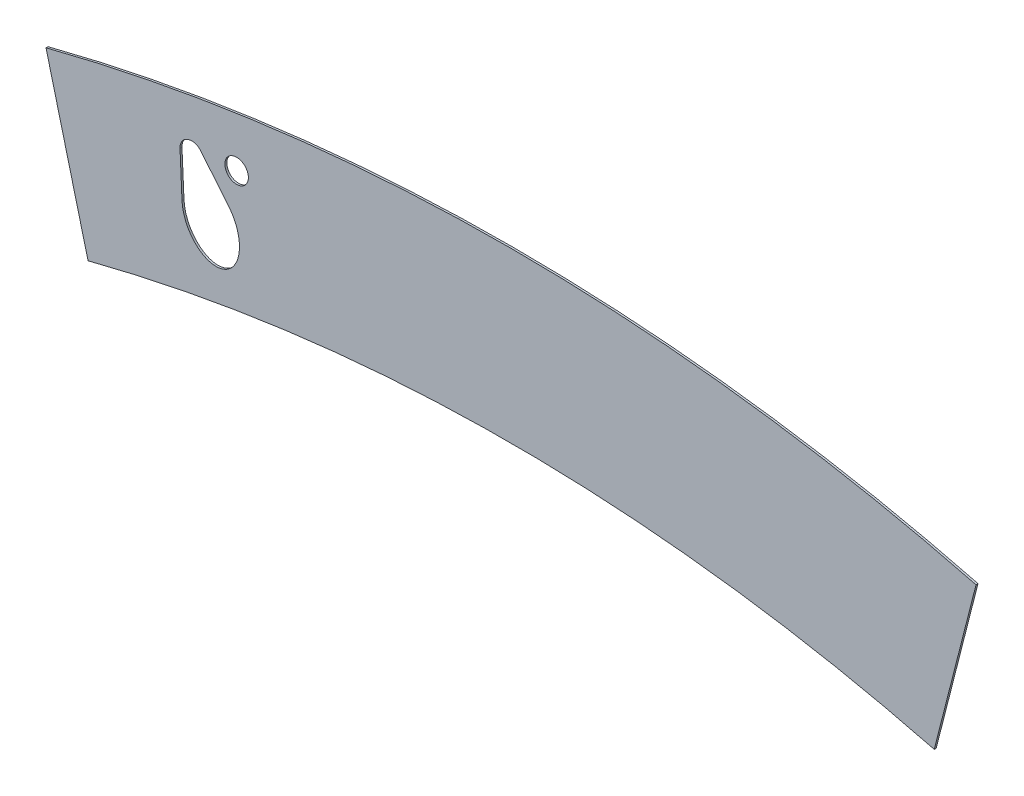
SolidWorks part; units mm, degrees
material "6061 Alloy"
ref_plane "front" through (0, 0, 0) normal (0, 0, 1) x (1, 0, 0)
ref_plane "top" through (0, 0, 0) normal (0, 1, 0) x (1, 0, 0)
ref_plane "right" through (0, 0, 0) normal (1, 0, 0) x (0, 0, -1)
sketch "Sketch1" plane through (0, 0, 0) normal (0, 0, 1) x (1, 0, 0)
  line L0 (0, 0) -> (0, -273.05) construction
  line L1 (0, 0) -> (383.281, 0) construction
  line L2 (-752.475, -95.2622) -> (-684.4284, -359.6974)
  line L3 (752.475, -95.2622) -> (684.8094, -359.7954)
  line L4 (-546.1, -49.7933) -> (-385.8603, -468.3234) construction
  line L5 (-535.6147, -127.7434) -> (-532.3846, -199.4546)
  line L6 (-501.8468, -114.8149) -> (-456.3599, -170.3475)
  arc A0 (752.475, -95.2622) -> (-752.475, -95.2622) centre (0, -3019.5266) ccw
  arc A1 (684.8094, -359.7954) -> (-684.4284, -359.6974) centre (0, -3019.5266) ccw
  circle A2 centre (-444.0174, -113.4618) radius 19.05
  arc A3 (-501.8468, -114.8149) -> (-535.6147, -127.7434) centre (-516.584, -126.8862) ccw
  ellipse E0 centre (-485.9328, -206.9441) end of major axis (-464.931, -261.7987) minor radius 44.45 (-532.3846, -199.4546) -> (-456.3599, -170.3475) ccw
  dimension "D1" = 3019.5266
  dimension "D5" = 20.95
  dimension "D7" = 38.1
  dimension "D12" = 19.05
  dimension "D2" = 1504.95
  dimension "D3" = 273.05
  dimension "D4" = 684.4284
  dimension "D6" = 546.1
  dimension "D8" = 168.275
  dimension "D9" = 88.9
  dimension "D10" = 58.7375
  dimension "D11" = 752.475
  dimension "D13" = 684.8094
  dimension "D14" = 82.55
  dimension "D15" = 444.0174
  dimension "D16" = 113.4618
  dimension "D17" = 73.7979
extrude "Base-Extrude" add sketch "Sketch1" against normal blind 3.175
